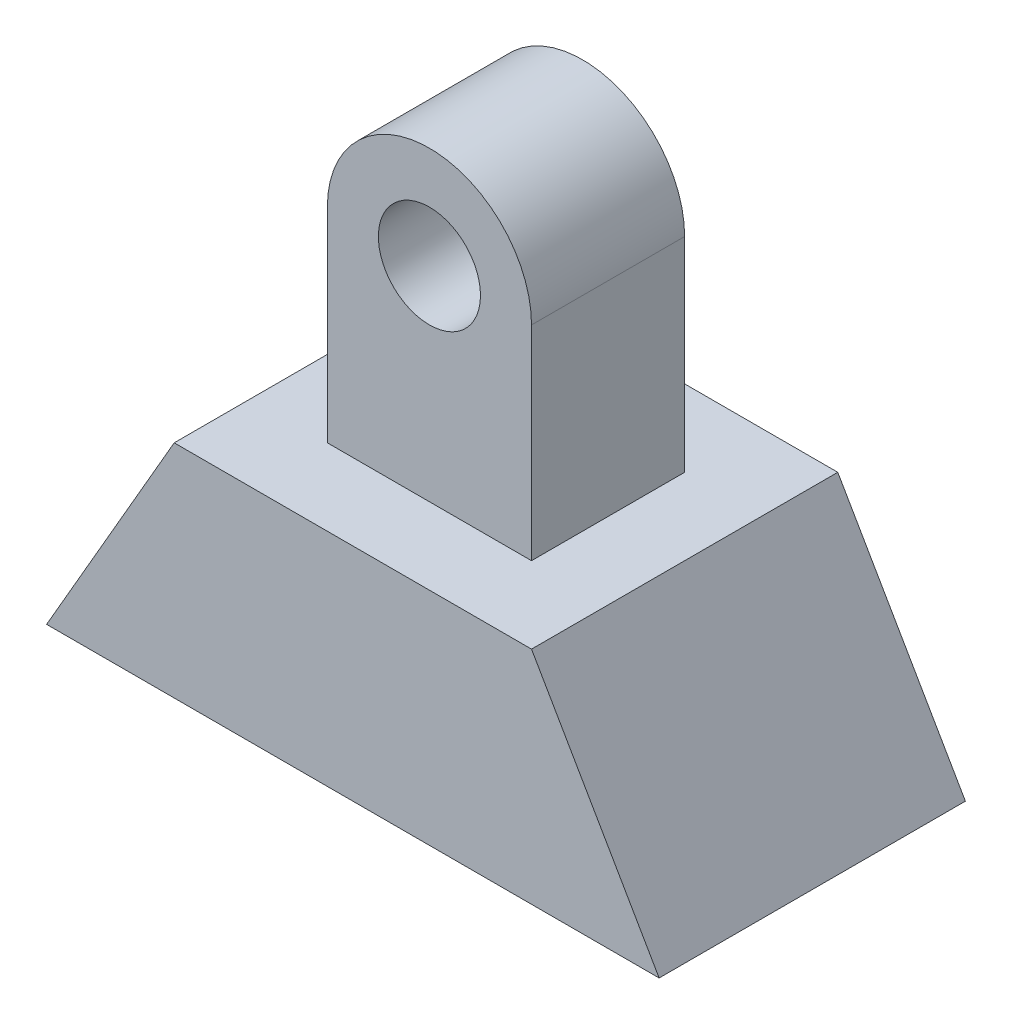
SolidWorks part; units mm, degrees
ref_plane "Ön Düzlem" through (0, 0, 0) normal (0, 0, 1) x (1, 0, 0)
ref_plane "Üst Düzlem" through (0, 0, 0) normal (0, 1, 0) x (1, 0, 0)
ref_plane "Sağ Düzlem" through (0, 0, 0) normal (1, 0, 0) x (0, 0, -1)
sketch "Çizim1" plane through (0, 0, 0) normal (0, 0, 1) x (1, 0, 0)
  line L0 (-60, -21.6506) -> (60, -21.6506)
  line L1 (60, -21.6506) -> (35, 21.6506)
  line L2 (35, 21.6506) -> (-35, 21.6506)
  line L3 (-35, 21.6506) -> (-60, -21.6506)
  point P2 (0, 21.6506)
  point P6 (-47.5, 0)
  dimension "D1" = 120
  dimension "D2" = 60
  dimension "D3" = 70
extrude "Yükseklik-Ekstrüzyon1" add sketch "Çizim1" along normal mid plane 60
sketch "Çizim2" plane through (0, 0, 0) normal (0, 0, 1) x (1, 0, 0)
  line L0 (-20, 21.6506) -> (-20, 61.6506)
  line L1 (35, 21.6506) -> (-35, 21.6506) construction
  line L2 (20, 21.6506) -> (20, 61.6506)
  line L3 (-20, 21.6506) -> (20, 21.6506)
  arc A0 (20, 61.6506) -> (-20, 61.6506) centre (0, 61.6506) ccw
  circle A1 centre (0, 61.6506) radius 10
  dimension "D1" = 40
  dimension "D3" = 20
  dimension "D2" = 40
extrude "Yükseklik-Ekstrüzyon2" add sketch "Çizim2" along normal mid plane 30
ref_plane "Plane2" through (0, 0, 0) normal (0, 0, 1) x (1, 0, 0)
sketch "Sketch2" plane through (0, 0, 0) normal (0, 0, 1) x (1, 0, 0)
  point P0 (0, 61.6506)
ref_plane "Plane3" through (0, 61.6506, 0) normal (0, 1, 0) x (1, 0, 0)
